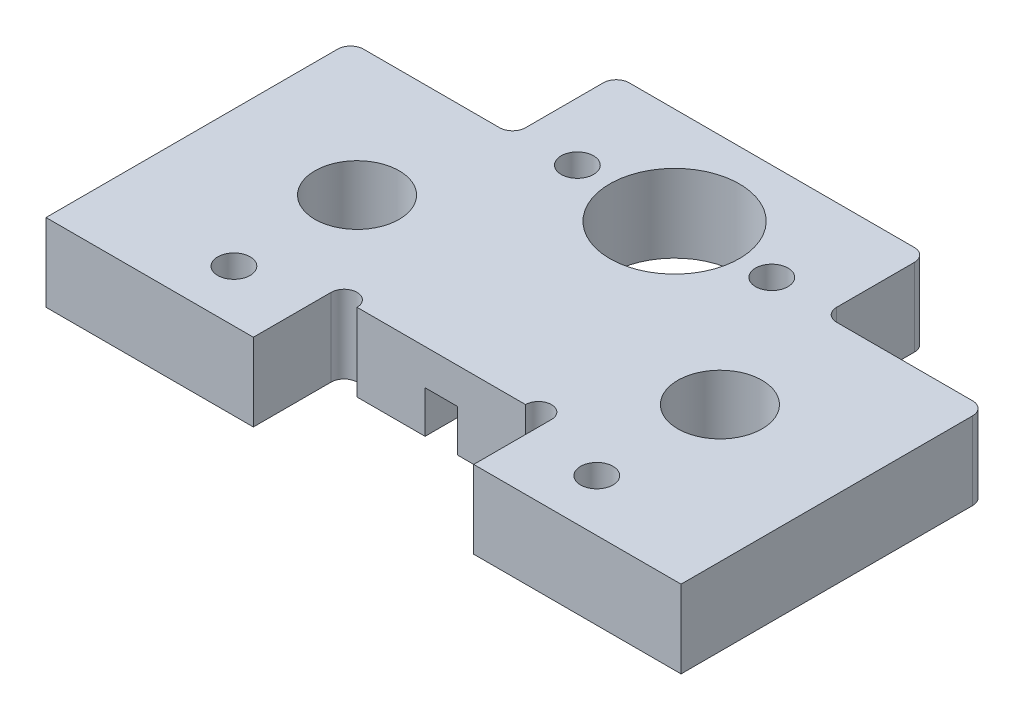
SolidWorks part; units mm, degrees
material "HDPE-green"
ref_plane "Front Plane" through (0, 0, 0) normal (0, 0, 1) x (1, 0, 0)
ref_plane "Top Plane" through (0, 0, 0) normal (0, 1, 0) x (1, 0, 0)
ref_plane "Right Plane" through (0, 0, 0) normal (1, 0, 0) x (0, 0, -1)
sketch "Sketch1" plane through (0, 0, 0) normal (0, 1, 0) x (1, 0, 0)
  line L1 (-49, 31.5) -> (49, 31.5)
  line L2 (-49, 31.5) -> (-49, -31.5)
  line L3 (-49, -31.5) -> (49, -31.5)
  line L4 (49, 31.5) -> (49, -31.5)
  line L5 (-49, 31.5) -> (49, -31.5) construction
  line L6 (-49, -31.5) -> (49, 31.5) construction
  point P0 (0, 0)
  dimension "D1" = 63
  dimension "D2" = 98
extrude "Boss-Extrude1" add sketch "Sketch1" along normal blind 12
sketch "Sketch2" plane through (0, 12, 0) normal (0, 1, 0) x (1, 0, 0)
  line L0 (0, -11.1414) -> (0, 34.2756) construction
  line L1 (49, 31.5) -> (-49, 31.5) construction
  line L2 (-20.0177, 16.5) -> (14.269, 16.5) construction
  circle A0 centre (0, 16.5) radius 10
  circle A1 centre (-28, -4.5) radius 6.5
  circle A2 centre (28, -4.5) radius 6.5
  circle A3 centre (-15, 16.5) radius 2.5
  circle A4 centre (15, 16.5) radius 2.5
  dimension "D1" = 20
  dimension "D2" = 28
  dimension "D3" = 21
  dimension "D4" = 28
  dimension "D5" = 21
  dimension "D6" = 15
  dimension "D7" = 5
  dimension "D8" = 5
  dimension "D9" = 15
  dimension "D10" = 15
  dimension "D11" = 13
  dimension "D12" = 13
extrude "Cut-Extrude1" cut sketch "Sketch2" against normal up to next
sketch "Sketch3" plane through (0, 12, 0) normal (0, 1, 0) x (1, 0, 0)
  line L0 (0, 0) -> (0, -27.5305) construction
  line L1 (17, -31.5) -> (-17, -31.5)
  line L2 (17, -31.5) -> (17, -19.5)
  line L3 (17, -19.5) -> (-17, -19.5)
  line L4 (-17, -31.5) -> (-17, -19.5)
  line L5 (17, -31.5) -> (-17, -19.5) construction
  line L6 (17, -19.5) -> (-17, -31.5) construction
  circle A1 centre (-28, -4.5) radius 6.5 construction
  point P0 (0, -25.5)
  dimension "D1" = 15
  dimension "D2" = 12
  dimension "D3" = 34
extrude "Cut-Extrude2" cut sketch "Sketch3" against normal up to next
hole_wizard "Ø5.0 (5) Diameter Hole1" positions "Sketch5" profile "Sketch4" hole size "Ø5.0" standard "ISO" end condition up to next
sketch "Sketch5" plane through (0, 12, 0) normal (0, 1, 0) x (-1, 0, 0)
  line L0 (49, 31.5) -> (17, 31.5) construction
  line L1 (-17, 31.5) -> (-49, 31.5) construction
  line L2 (-49, 31.5) -> (-49, -31.5) construction
  line L3 (49, -31.5) -> (49, 31.5) construction
  point P0 (28, 23.5)
  point P1 (-28, 23.5)
  dimension "D1" = 8
  dimension "D2" = 8
  dimension "D3" = 21
  dimension "D4" = 21
sketch "Sketch4" plane through (-28, 12, 23.5) normal (1, 0, 0) x (0, 0, 1)
  line L0 (0, 0) -> (0, 12)
  line L1 (0, 12) -> (2.5, 12)
  line L2 (2.5, 12) -> (2.5, 0)
  line L5 (2.5, 0) -> (0, 0)
  line L11 (0, -6.35) -> (0, 107.95) construction
  dimension "Thru Hole Dia." = 5
  dimension "Thru Hole Depth" = 12
sketch "Sketch11" plane through (0, 12, 0) normal (0, 1, 0) x (-1, 0, 0)
  line L1 (49, -31.5) -> (24, -31.5)
  line L2 (49, -31.5) -> (49, -15.5)
  line L3 (49, -15.5) -> (24, -15.5)
  line L4 (24, -31.5) -> (24, -15.5)
  dimension "D1" = 16
  dimension "D2" = 25
extrude "Cut-Extrude3" cut sketch "Sketch11" against normal up to next
mirror "Mirror1" about plane through (0, 0, 0) normal (1, 0, 0) of "Cut-Extrude3"
sketch "Sketch12" plane through (0, 12, 0) normal (0, 1, 0) x (1, 0, 0)
  line L0 (17, -19.5) -> (-17, -19.5) construction
  line L1 (-17, -19.5) -> (-13, -19.5)
  line L2 (13, -19.5) -> (17, -19.5)
  arc A0 (-17, -19.5) -> (-13, -19.5) centre (-15, -19.5) cw
  arc A1 (17, -19.5) -> (13, -19.5) centre (15, -19.5) ccw
  dimension "D1" = 2
  dimension "D2" = 2
extrude "Cut-Extrude4" cut sketch "Sketch12" against normal up to next
fillet "Fillet1" radius 2 6 edges at (49, 6, -15.5) (24, 6, -15.5) (24, 6, -31.5) (-24, 6, -31.5) (-24, 6, -15.5) (-49, 6, -15.5)
sketch "Sketch18" plane through (-30.4471, 0, 87.6825) normal (0, -1, 0) x (1, 0, 0)
  line L0 (26.4471, -80.1825) -> (34.4471, -80.1825) construction
  line L1 (26.4471, -78.1825) -> (34.4471, -78.1825)
  line L2 (26.4471, -82.1825) -> (34.4471, -82.1825)
  line L3 (30.4471, -65.9679) -> (30.4471, -87.6825) construction
  line L5 (17.4471, -68.1825) -> (43.4471, -68.1825) construction
  arc A0 (26.4471, -78.1825) -> (26.4471, -82.1825) centre (26.4471, -80.1825) ccw
  arc A1 (34.4471, -82.1825) -> (34.4471, -78.1825) centre (34.4471, -80.1825) ccw
  point P2 (30.4471, -80.1825)
  dimension "D1" = 8
  dimension "D2" = 2
  dimension "D3" = 12
extrude "Cut-Extrude7" cut sketch "Sketch18" against normal blind 8
sketch "Sketch20" plane through (-30.4471, 0, 87.6825) normal (0, -1, 0) x (1, 0, 0)
  line L0 (30.4471, -47.9543) -> (30.4471, -85.1825) construction
  line L1 (32.9471, -47.9543) -> (32.9471, -85.1825)
  line L2 (27.9471, -47.9543) -> (27.9471, -85.1825)
  line L4 (17.4471, -68.1825) -> (43.4471, -68.1825) construction
  arc A0 (32.9471, -47.9543) -> (27.9471, -47.9543) centre (30.4471, -47.9543) ccw
  arc A1 (27.9471, -85.1825) -> (32.9471, -85.1825) centre (30.4471, -85.1825) ccw
  point P2 (30.4471, -66.5684)
  point P7 (30.4471, -68.1825)
  dimension "D1" = 17
  dimension "D2" = 2.5
extrude "Cut-Extrude8" cut sketch "Sketch20" against normal blind 6.5
